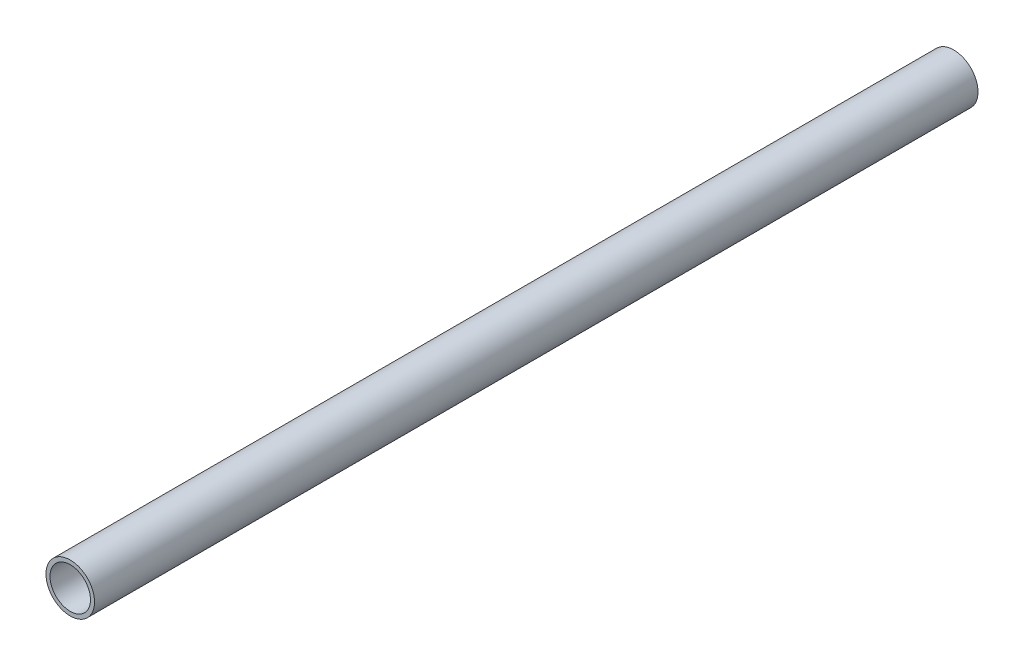
SolidWorks part; units mm, degrees
ref_plane "Plan de face" through (0, 0, 0) normal (0, 0, 1) x (1, 0, 0)
ref_plane "Plan de dessus" through (0, 0, 0) normal (0, 1, 0) x (1, 0, 0)
ref_plane "Plan de droite" through (0, 0, 0) normal (1, 0, 0) x (0, 0, -1)
sketch "Esquisse1" plane through (0, 0, 0) normal (0, 0, 1) x (1, 0, 0)
  circle A0 centre (0, 0) radius 15
extrude "Extru.-Mince1" add sketch "Esquisse1" along normal blind 655 thin
